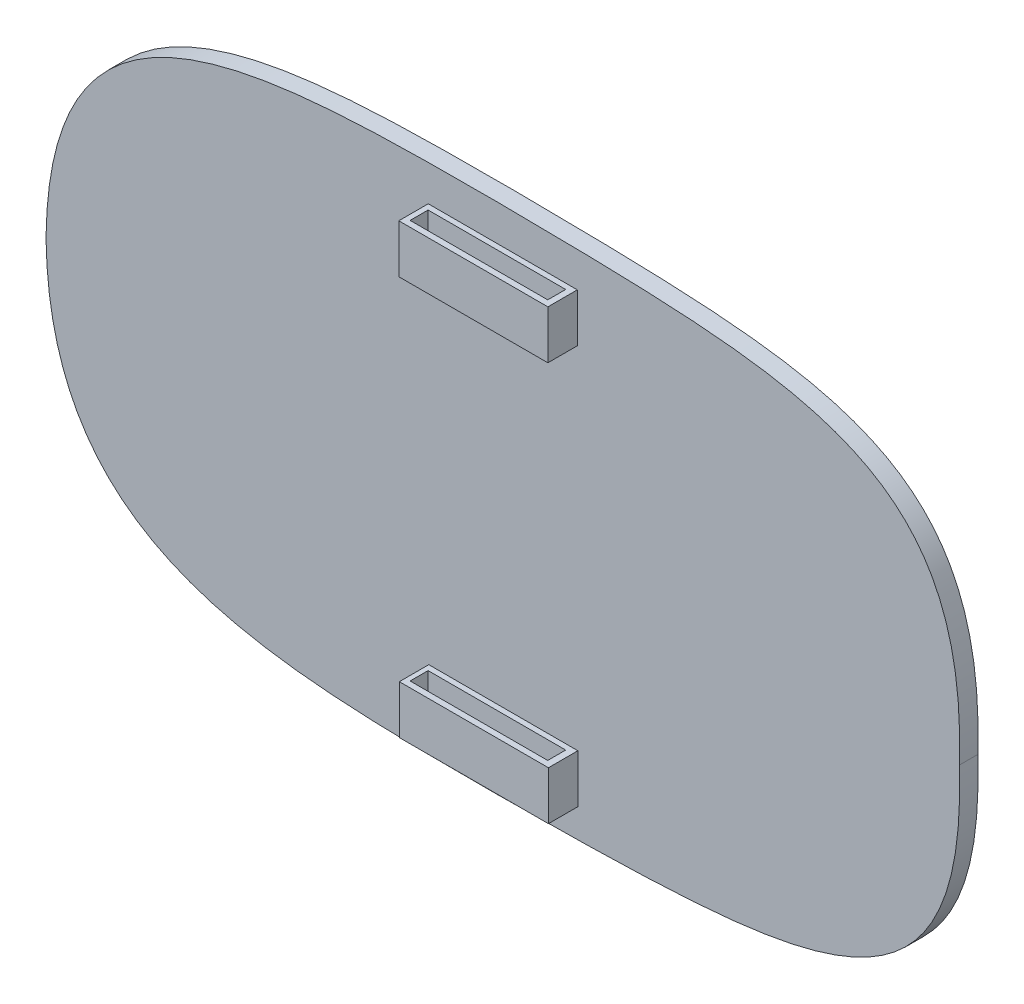
SolidWorks part; units mm, degrees
ref_plane "Front Plane" through (0, 0, 0) normal (0, 0, 1) x (1, 0, 0)
ref_plane "Top Plane" through (0, 0, 0) normal (0, 1, 0) x (1, 0, 0)
ref_plane "Right Plane" through (0, 0, 0) normal (1, 0, 0) x (0, 0, -1)
sketch "Sketch3" plane through (0, 0, 0) normal (0, 0, 1) x (1, 0, 0)
  spline S0 degree 3 poles (-62.0645, -0.0046) (-61.6219, -32.5599) (-30.1745, -35.196) (40.8554, -34.4947) (63.0683, -31.0445) (62.0438, -0.0046) knots 0 0 0 0 0.421952 0.521952 1 1 1 1
  spline S1 degree 3 poles (-62.0645, -0.0046) (-61.6219, 32.5506) (-30.1745, 35.1867) (40.8554, 34.4854) (63.0683, 31.0352) (62.0438, -0.0046) knots 0 0 0 0 0.421952 0.521952 1 1 1 1
  point P2 (0, 0)
  point P5 (2.657, -34.8456)
  point P8 (62.0438, -0.0046)
  point P10 (-62.0645, 0.0086)
extrude "Boss-Extrude1" add sketch "Sketch3" along normal blind 2.5 contours S0 S1
sketch "Sketch4" plane through (0, 0, 0) normal (0, 0, 1) x (1, 0, 0)
  circle A0 centre (51.0092, 21.8084) radius 2.75
  circle A1 centre (-55.2862, 0) radius 2.75
  circle A2 centre (52.863, -19.1829) radius 2.75
  dimension "D1" = 5.5
extrude "Cut-Extrude1" cut sketch "Sketch4" along normal blind 1.7
sketch "Sketch6" plane through (0, 0, 2.5) normal (0, 0, 1) x (1, 0, 0)
  line L1 (10.1274, 29.9549) -> (-10.1274, 29.9549)
  line L2 (10.1274, 29.9549) -> (10.1274, 23.3704)
  line L3 (10.1274, 23.3704) -> (-10.1274, 23.3704)
  line L4 (-10.1274, 29.9549) -> (-10.1274, 23.3704)
  line L5 (10.1274, 29.9549) -> (-10.1274, 23.3704) construction
  line L6 (10.1274, 23.3704) -> (-10.1274, 29.9549) construction
  point P0 (0, 26.6627)
extrude "Boss-Extrude2" add sketch "Sketch6" along normal blind 4
sketch "Sketch7" plane through (0, 0, 2.5) normal (0, 0, 1) x (1, 0, 0)
  line L0 (57.0656, 0) -> (-57.0656, 0) construction
  line L1 (10.2009, -24.2419) -> (-10.0539, -24.2419)
  line L2 (10.2009, -24.2419) -> (10.2009, -30.8264)
  line L3 (10.2009, -30.8264) -> (-10.0539, -30.8264)
  line L4 (-10.0539, -24.2419) -> (-10.0539, -30.8264)
  line L5 (10.2009, -24.2419) -> (-10.0539, -30.8264) construction
  line L6 (10.2009, -30.8264) -> (-10.0539, -24.2419) construction
  line L7 (0, -36.9621) -> (0, 36.9621) construction
  point P0 (0.0735, -27.5341)
  point P4 (0, 0)
  point P12 (0, 0)
extrude "Boss-Extrude3" add sketch "Sketch7" along normal blind 4
sketch "Sketch8" plane through (0, 0, 0) normal (0, 1, 0) x (1, 0, 0)
  line L1 (9.2934, -3.2447) -> (-9.4031, -3.2447)
  line L2 (9.2934, -3.2447) -> (9.2934, -5.6887)
  line L3 (9.2934, -5.6887) -> (-9.4031, -5.6887)
  line L4 (-9.4031, -3.2447) -> (-9.4031, -5.6887)
  line L5 (9.2934, -3.2447) -> (-9.4031, -5.6887) construction
  line L6 (9.2934, -5.6887) -> (-9.4031, -3.2447) construction
  point P0 (-0.0549, -4.4667)
  point P5 (9.2934, -3.1633)
  point P6 (-9.3624, -5.6887)
  point P7 (-9.4031, -3.2447)
extrude "Cut-Extrude2" cut sketch "Sketch8" against normal blind 44 and the other way blind 53
